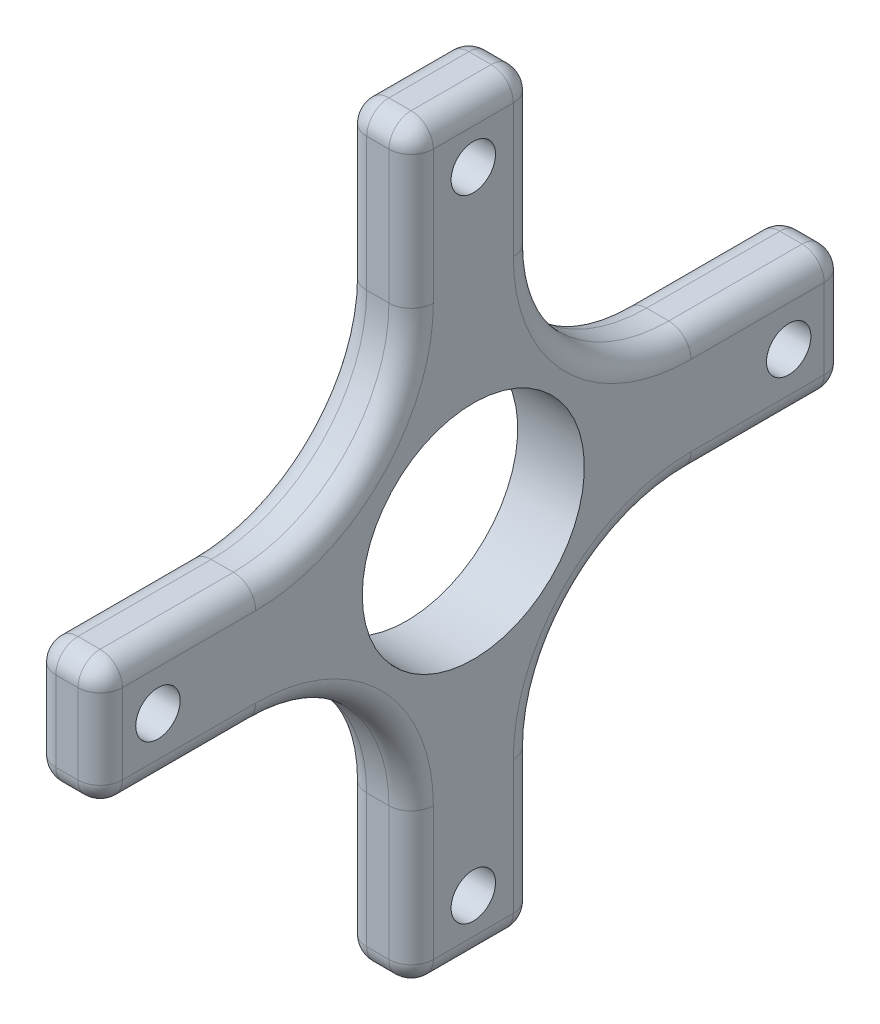
SolidWorks part; units mm, degrees
ref_plane "Front Plane" through (0, 0, 0) normal (0, 0, 1) x (1, 0, 0)
ref_plane "Top Plane" through (0, 0, 0) normal (0, 1, 0) x (1, 0, 0)
ref_plane "Right Plane" through (0, 0, 0) normal (1, 0, 0) x (0, 0, -1)
sketch "Sketch1" plane through (664.9259, 0, 0) normal (-1, 0, 0) x (0, 0, 1)
  line L0 (1323.3179, 920.6327) -> (1328.9179, 920.6327)
  line L1 (1328.9179, 920.6327) -> (1328.9179, 913.6327)
  line L2 (1335.9179, 906.6327) -> (1342.9179, 906.6327)
  line L3 (1342.9179, 906.6327) -> (1342.9179, 901.0327)
  line L4 (1342.9179, 901.0327) -> (1335.9179, 901.0327)
  line L5 (1328.9179, 894.0327) -> (1328.9179, 887.0327)
  line L6 (1328.9179, 887.0327) -> (1323.3179, 887.0327)
  line L7 (1323.3179, 887.0327) -> (1323.3179, 894.0327)
  line L8 (1316.3179, 901.0327) -> (1309.3179, 901.0327)
  line L9 (1309.3179, 901.0327) -> (1309.3179, 906.6327)
  line L10 (1309.3179, 906.6327) -> (1316.3179, 906.6327)
  line L11 (1323.3179, 913.6327) -> (1323.3179, 920.6327)
  line L12 (1327.1179, 918.0327) -> (1325.1179, 918.0327) construction
  line L13 (1326.1179, 200933.819) -> (1326.1179, -199126.1536) construction
  arc A0 (1335.9179, 906.6327) -> (1328.9179, 913.6327) centre (1335.9179, 913.6327) cw
  arc A1 (1328.9179, 894.0327) -> (1335.9179, 901.0327) centre (1335.9179, 894.0327) cw
  arc A2 (1323.3179, 894.0327) -> (1316.3179, 901.0327) centre (1316.3179, 894.0327) ccw
  arc A3 (1316.3179, 906.6327) -> (1323.3179, 913.6327) centre (1316.3179, 913.6327) ccw
  circle A4 centre (1326.1179, 918.0327) radius 1
  circle A5 centre (1311.9179, 903.8327) radius 1
  circle A6 centre (1340.3179, 903.8327) radius 1
  circle A7 centre (1326.1179, 889.6327) radius 1
  circle A8 centre (1326.1179, 903.8327) radius 5
  point P22 (1328.9179, 906.6327)
  dimension "D1" = 7
  dimension "D2" = 7
  dimension "D3" = 7
  dimension "D4" = 7
extrude "Boss-Extrude1" add sketch "Sketch1" along normal blind 3
fillet "Fillet1" radius 1 8 edges at (663.4259, 906.6327, 1342.9179) (663.4259, 901.0327, 1342.9179) (663.4259, 887.0327, 1328.9179) (663.4259, 887.0327, 1323.3179) (663.4259, 901.0327, 1309.3179) (663.4259, 920.6327, 1323.3179) (663.4259, 906.6327, 1309.3179) (663.4259, 920.6327, 1328.9179)
fillet "Fillet3" radius 1 48 edges at (661.9259, 901.3256, 1342.6251) (661.9259, 901.0327, 1338.9179) (661.9259, 898.9824, 1330.9682) (661.9259, 891.0327, 1328.9179) (661.9259, 887.3256, 1328.6251) (661.9259, 887.0327, 1326.1179) (661.9259, 887.3256, 1323.6108) (661.9259, 891.0327, 1323.3179) (661.9259, 898.9824, 1321.2677) (661.9259, 901.0327, 1313.3179) (661.9259, 901.3256, 1309.6108) (661.9259, 903.8327, 1309.3179) (661.9259, 906.3398, 1309.6108) (661.9259, 906.6327, 1313.3179) (661.9259, 908.6829, 1321.2677) (661.9259, 916.6327, 1323.3179) (661.9259, 920.3398, 1323.6108) (661.9259, 920.6327, 1326.1179) (661.9259, 920.3398, 1328.6251) (661.9259, 916.6327, 1328.9179) (661.9259, 908.6829, 1330.9682) (661.9259, 906.6327, 1338.9179) (661.9259, 906.3398, 1342.6251) (661.9259, 903.8327, 1342.9179) (664.9259, 908.6829, 1330.9682) (664.9259, 916.6327, 1328.9179) (664.9259, 920.3398, 1328.6251) (664.9259, 920.6327, 1326.1179) (664.9259, 920.3398, 1323.6108) (664.9259, 916.6327, 1323.3179) (664.9259, 908.6829, 1321.2677) (664.9259, 906.6327, 1313.3179) (664.9259, 906.3398, 1309.6108) (664.9259, 903.8327, 1309.3179) (664.9259, 901.3256, 1309.6108) (664.9259, 901.0327, 1313.3179) (664.9259, 898.9824, 1321.2677) (664.9259, 891.0327, 1323.3179) (664.9259, 887.3256, 1323.6108) (664.9259, 887.0327, 1326.1179) (664.9259, 887.3256, 1328.6251) (664.9259, 891.0327, 1328.9179) (664.9259, 898.9824, 1330.9682) (664.9259, 901.0327, 1338.9179) (664.9259, 901.3256, 1342.6251) (664.9259, 903.8327, 1342.9179) (664.9259, 906.3398, 1342.6251) (664.9259, 906.6327, 1338.9179)
